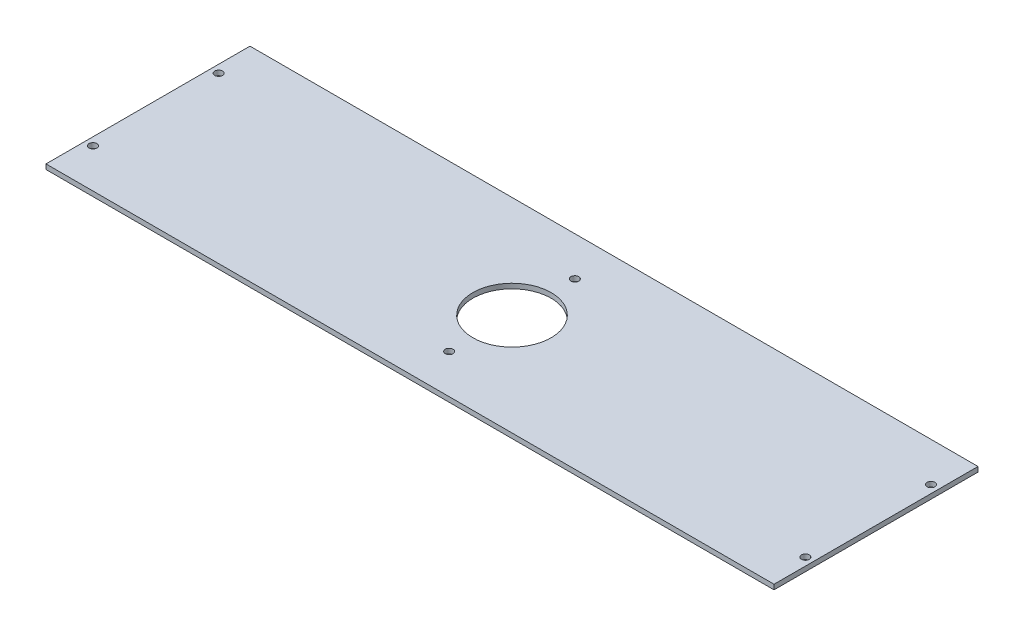
SolidWorks part; units mm, degrees
ref_plane "Front Plane" through (0, 0, 0) normal (0, 0, 1) x (1, 0, 0)
ref_plane "Top Plane" through (0, 0, 0) normal (0, 1, 0) x (1, 0, 0)
ref_plane "Right Plane" through (0, 0, 0) normal (1, 0, 0) x (0, 0, -1)
sketch "Sketch1" plane through (0, 0, 0) normal (0, 1, 0) x (1, 0, 0)
  line L1 (-113.8302, 59.2962) -> (258.1698, 59.2962)
  line L2 (-113.8302, 59.2962) -> (-113.8302, -44.9238)
  line L3 (-113.8302, -44.9238) -> (258.1698, -44.9238)
  line L4 (258.1698, 59.2962) -> (258.1698, -44.9238)
extrude "Boss-Extrude1" add sketch "Sketch1" along normal blind 2.5 contours L1 L4 L3 L2
sketch "Sketch2" plane through (0, 2.5, 0) normal (0, 1, 0) x (1, 0, 0)
  line L0 (-113.8302, 59.2962) -> (-109.8302, 59.2962)
  line L1 (-113.8302, 59.2962) -> (258.1698, 59.2962) construction
  line L2 (-113.8302, 59.2962) -> (-113.8302, 39.2962)
  line L3 (-113.8302, 59.2962) -> (-113.8302, -44.9238) construction
  line L4 (-109.8302, 59.2962) -> (-113.8302, 59.2962)
  line L5 (-109.8302, 59.2962) -> (-109.8302, 39.2962)
  line L6 (-113.8302, 59.2962) -> (-113.8302, 39.2962)
  line L7 (-109.8302, 39.2962) -> (-113.8302, 39.2962)
  line L8 (-113.8302, -44.9238) -> (-109.8302, -44.9238)
  line L9 (-113.8302, -44.9238) -> (-113.8302, -24.9238)
  line L10 (-109.8302, -44.9238) -> (-113.8302, -44.9238)
  line L11 (-109.8302, -44.9238) -> (-109.8302, -24.9238)
  line L12 (-113.8302, -44.9238) -> (-113.8302, -24.9238)
  line L13 (-109.8302, -24.9238) -> (-113.8302, -24.9238)
  line L14 (258.1698, -44.9238) -> (254.1698, -44.9238)
  line L15 (258.1698, -44.9238) -> (258.1698, -24.9238)
  line L16 (254.1698, -44.9238) -> (258.1698, -44.9238)
  line L17 (254.1698, -44.9238) -> (254.1698, -24.9238)
  line L18 (258.1698, -44.9238) -> (258.1698, -24.9238)
  line L19 (254.1698, -24.9238) -> (258.1698, -24.9238)
  line L20 (-113.8302, -44.9238) -> (258.1698, -44.9238) construction
  line L22 (255.0869, -37.1853) -> (259.0869, -37.1853)
  line L23 (255.0869, -37.1853) -> (255.0869, -41.1853)
  line L24 (259.0869, -37.1853) -> (255.0869, -37.1853)
  line L25 (259.0869, -37.1853) -> (259.0869, -41.1853)
  line L26 (255.0869, -37.1853) -> (255.0869, -41.1853)
  line L27 (259.0869, -41.1853) -> (255.0869, -41.1853)
  line L28 (258.1698, 59.2962) -> (254.1698, 59.2962)
  line L29 (258.1698, 59.2962) -> (258.1698, 39.2962)
  line L30 (254.1698, 59.2962) -> (258.1698, 59.2962)
  line L31 (254.1698, 59.2962) -> (254.1698, 39.2962)
  line L32 (258.1698, 59.2962) -> (258.1698, 39.2962)
  line L33 (254.1698, 39.2962) -> (258.1698, 39.2962)
  circle A0 centre (-109.8302, 39.2962) radius 2
  circle A1 centre (-109.8302, -24.9238) radius 2
  circle A2 centre (254.1698, -24.9238) radius 2
  circle A3 centre (259.0869, -41.1853) radius 2
  circle A4 centre (254.1698, 39.2962) radius 2
extrude "Cut-Extrude1" cut sketch "Sketch2" against normal blind 10 contours L7 A0 L5 | L5 A0 L7 | L33 A4 L31 | L31 A4 L33 | A1 | A2
sketch "Sketch3" plane through (0, 2.5, 0) normal (0, 1, 0) x (1, 0, 0)
  line L0 (-113.8302, 59.2962) -> (-113.8302, 39.2962)
  line L1 (-113.8302, 59.2962) -> (-113.8302, -44.9238) construction
  line L2 (-113.8302, 39.2962) -> (258.1698, 39.2962)
  line L3 (258.1698, 59.2962) -> (258.1698, -44.9238) construction
  line L4 (-113.8302, -44.9238) -> (-113.8302, -24.9238)
  line L5 (-113.8302, -24.9238) -> (258.1698, -24.9238)
  circle A0 centre (72.1698, 39.2962) radius 2
  circle A1 centre (72.1698, -24.9238) radius 2
extrude "Cut-Extrude2" cut sketch "Sketch3" against normal blind 10 contours A1 | A0
sketch "Sketch4" plane through (0, 2.5, 0) normal (0, 1, 0) x (1, 0, 0)
  line L0 (72.1698, 39.2962) -> (72.1698, -24.9238)
  circle A0 centre (72.1698, 7.1862) radius 20
extrude "Cut-Extrude3" cut sketch "Sketch4" against normal blind 26 contours L0 A0 | L0 A0
